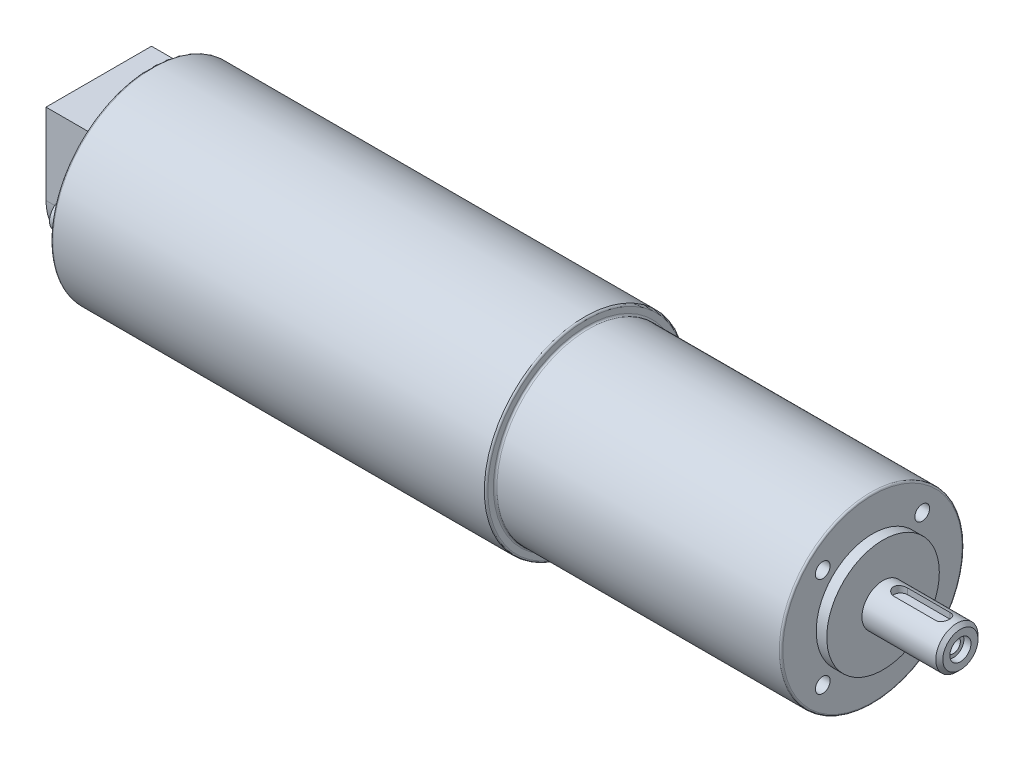
SolidWorks part; units mm, degrees
ref_plane "Front Plane" through (0, 0, 0) normal (0, 0, 1) x (1, 0, 0)
ref_plane "Top Plane" through (0, 0, 0) normal (0, 1, 0) x (1, 0, 0)
ref_plane "Right Plane" through (0, 0, 0) normal (1, 0, 0) x (0, 0, -1)
sketch "Sketch1" plane through (0, 0, 0) normal (1, 0, 0) x (0, 0, -1)
  circle A0 centre (0, 0) radius 28.575
  dimension "D1" = 57.15
extrude "Boss-Extrude1" add sketch "Sketch1" along normal blind 123.7
ref_plane "Plane3" through (205, 0, 0) normal (-1, 0, 0) x (0, 0, 1)
sketch "Sketch2" plane through (205, 0, 0) normal (1, 0, 0) x (0, 0, -1)
  circle A0 centre (0, 0) radius 26
  dimension "D1" = 52
extrude "Boss-Extrude2" add sketch "Sketch2" against normal up to surface (81.3 mm away) up to face at (123.7, 0, -28.575)
sketch "Sketch3" plane through (205, 0, 0) normal (1, 0, 0) x (0, 0, -1)
  circle A0 centre (0, 0) radius 16
  dimension "D1" = 32
extrude "Boss-Extrude3" add sketch "Sketch3" along normal blind 3
sketch "Sketch4" plane through (208, 0, 0) normal (1, 0, 0) x (0, 0, -1)
  circle A0 centre (0, 0) radius 6
  dimension "D1" = 12
extrude "Boss-Extrude4" add sketch "Sketch4" along normal blind 22
chamfer "Chamfer1" distance 1 angle 45 1 edges at (230, 0, -6)
sketch "Sketch6" plane through (230, 0, 0) normal (1, 0, 0) x (0, 0, -1)
  line L0 (0, 6) -> (0, -6) construction
  line L1 (-6, 0) -> (6, 0) construction
  circle A1 centre (0, 0) radius 6 construction
  circle A2 centre (0, 0) radius 6 construction
  circle A3 centre (0, 0) radius 3
  point P2 (0, 0)
  dimension "D1" = 6
extrude "Cut-Extrude1" cut sketch "Sketch6" against normal blind 2
fillet "Fillet1" radius 0.5 4 edges at (0, 0, -28.575) (123.7, 0, -28.575) (123.7, 0, -26) (205, 0, -26)
hole_wizard "M4 Tapped Hole1" positions "3DSketch2" profile "Sketch8" tap size "M4" standard "ISO"
sketch3d "3DSketch2"
  point P0 (0, 0, 0)
  point P3 (230, 0, 0)
sketch "Sketch8" plane through (230, 0, 0) normal (0, 1, 0) x (0, 0, -1)
  line L0 (0, 0) -> (0, 12.9914)
  line L1 (0, 12.9914) -> (1.65, 12)
  line L2 (1.65, 12) -> (1.65, 10)
  line L3 (1.65, 10) -> (2, 10)
  line L4 (2, 10) -> (2, 0)
  line L5 (2, 0) -> (0, 0)
  line L10 (0, 12.9914) -> (-1.65, 12) construction
  line L11 (0, -6.35) -> (0, 107.95) construction
  dimension "Tap Drill Dia." = 3.3
  dimension "Tap Drill Depth" = 12
  dimension "Thread Major Dia." = 4
  dimension "Thread Depth" = 10
  dimension "Drill Angle" = 118
sketch "Sketch9" plane through (205, 0, 0) normal (1, 0, 0) x (0, 0, -1)
  line L0 (14.1421, 14.1421) -> (-14.1421, -14.1421) construction
  line L1 (-14.1421, 14.1421) -> (14.1421, -14.1421) construction
  line L2 (0, 0) -> (20, 0) construction
  circle A0 centre (0, 0) radius 20 construction
  dimension "D1" = 40
  dimension "D2" = 90
  dimension "D3" = 45
hole_wizard "M5 Tapped Hole1" positions "3DSketch3" profile "Sketch10" tap size "M5" standard "ISO"
sketch3d "3DSketch3"
  point P0 (205, 14.1421, -14.1421)
  point P3 (205, 14.1421, 14.1421)
  point P6 (205, -14.1421, -14.1421)
  point P9 (205, -14.1421, 14.1421)
sketch "Sketch10" plane through (205, 14.1421, -14.1421) normal (0, 1, 0) x (0, 0, -1)
  line L0 (0, 0) -> (0, 13.6618)
  line L1 (0, 13.6618) -> (2.1, 12.4)
  line L2 (2.1, 12.4) -> (2.1, 0)
  line L5 (2.1, 0) -> (0, 0)
  line L10 (0, 13.6618) -> (-2.1, 12.4) construction
  line L11 (0, -6.35) -> (0, 107.95) construction
  dimension "Tap Drill Dia." = 4.2
  dimension "Tap Drill Depth" = 12.4
  dimension "Drill Angle" = 118
cosmetic thread "Hole Thread1" parameters "D1"=10, "D2"=5
cosmetic thread "Hole Thread2" parameters "D1"=10, "D2"=5
cosmetic thread "Hole Thread3" parameters "D1"=10, "D2"=5
cosmetic thread "Hole Thread4" parameters "D1"=10, "D2"=5
ref_plane "Plane1" through (0, 8, 0) normal (0, 1, 0) x (1, 0, 0)
sketch "Sketch12" plane through (0, 8, 0) normal (0, 1, 0) x (1, 0, 0)
  line L0 (208, 0) -> (230, 0) construction
  line L1 (208, -16) -> (208, 16) construction
  line L2 (211, 2) -> (227, -2) construction
  line L3 (225.1, 2) -> (212.9, 2)
  line L4 (227, 0.1) -> (227, -0.1)
  line L5 (225.1, -2) -> (212.9, -2)
  line L6 (211, 0.1) -> (211, -0.1)
  line L7 (227, 2) -> (211, -2) construction
  arc A0 (212.9, -2) -> (211, -0.1) centre (212.9, -0.1) cw
  arc A1 (225.1, 2) -> (227, 0.1) centre (225.1, 0.1) cw
  arc A2 (227, -0.1) -> (225.1, -2) centre (225.1, -0.1) cw
  arc A3 (212.9, 2) -> (211, 0.1) centre (212.9, 0.1) ccw
  point P9 (219, 0)
  point P10 (219, 0)
  point P11 (219, 0)
  dimension "D3" = 1.9
  dimension "D1" = 16
  dimension "D2" = 4
extrude "Boss-Extrude5" [suppressed] add sketch "Sketch12" against normal up to next
fillet "Fillet2" [suppressed] radius 0.25
sketch "Sketch13" plane through (0, 0, 0) normal (-1, 0, 0) x (0, 0, 1)
  line L0 (0, 28.575) -> (0, -28.575) construction
  line L1 (-15, 18.575) -> (15, 18.575)
  line L2 (15, 18.575) -> (15, -4.425)
  line L3 (-15, 18.575) -> (-15, -4.425)
  line L4 (28.575, 0) -> (-28.575, 0) construction
  circle A0 centre (0, 0) radius 28.575 construction
  arc A1 (-15, -4.425) -> (15, -4.425) centre (0, -4.425) ccw
  point P11 (0, 18.575)
  dimension "D1" = 10
  dimension "D2" = 15
  dimension "D3" = 23
extrude "Boss-Extrude6" add sketch "Sketch13" along normal blind 15
sketch "Sketch14" plane through (0, 0, 0) normal (-1, 0, 0) x (0, 0, 1)
  line L0 (20, 4) -> (15, 6.3315)
  line L1 (15, -4.425) -> (15, 18.575) construction
  line L2 (6, 0) -> (-6, 0) construction
  line L3 (24, 0) -> (16, 0) construction
  line L4 (20, -4) -> (15, -6.3315)
  line L5 (15, -6.3315) -> (15, 6.3315)
  line L6 (0, 28.575) -> (0, -28.575) construction
  line L7 (-24, 0) -> (-16, 0) construction
  line L8 (-20, -4) -> (-15, -6.3315)
  line L9 (-15, -6.3315) -> (-15, 6.3315)
  line L10 (-20, 4) -> (-15, 6.3315)
  circle A0 centre (20, 0) radius 1.75
  arc A1 (20, -4) -> (20, 4) centre (20, 0) ccw
  circle A2 centre (0, 0) radius 28.575 construction
  circle A3 centre (-20, 0) radius 1.75
  arc A4 (-20, -4) -> (-20, 4) centre (-20, 0) cw
  dimension "D1" = 3.5
  dimension "D2" = 8
  dimension "D3" = 20
  dimension "D4" = 25
extrude "Boss-Extrude7" add sketch "Sketch14" along normal blind 5
ref_plane "Plane2" through (0, 4, 0) normal (0, 1, 0) x (1, 0, 0)
sketch "Sketch15" plane through (0, 4, 0) normal (0, 1, 0) x (1, 0, 0)
  line L0 (225, 0) -> (213, 0) construction
  line L1 (225, -2) -> (213, -2)
  line L2 (225, 2) -> (213, 2)
  line L3 (230, -5) -> (230, 5) construction
  arc A0 (225, -2) -> (225, 2) centre (225, 0) ccw
  arc A1 (213, 2) -> (213, -2) centre (213, 0) ccw
  point P3 (219, 0)
  dimension "D1" = 4
  dimension "D2" = 11
  dimension "D3" = 12
extrude "Cut-Extrude3" cut sketch "Sketch15" along normal blind 10
